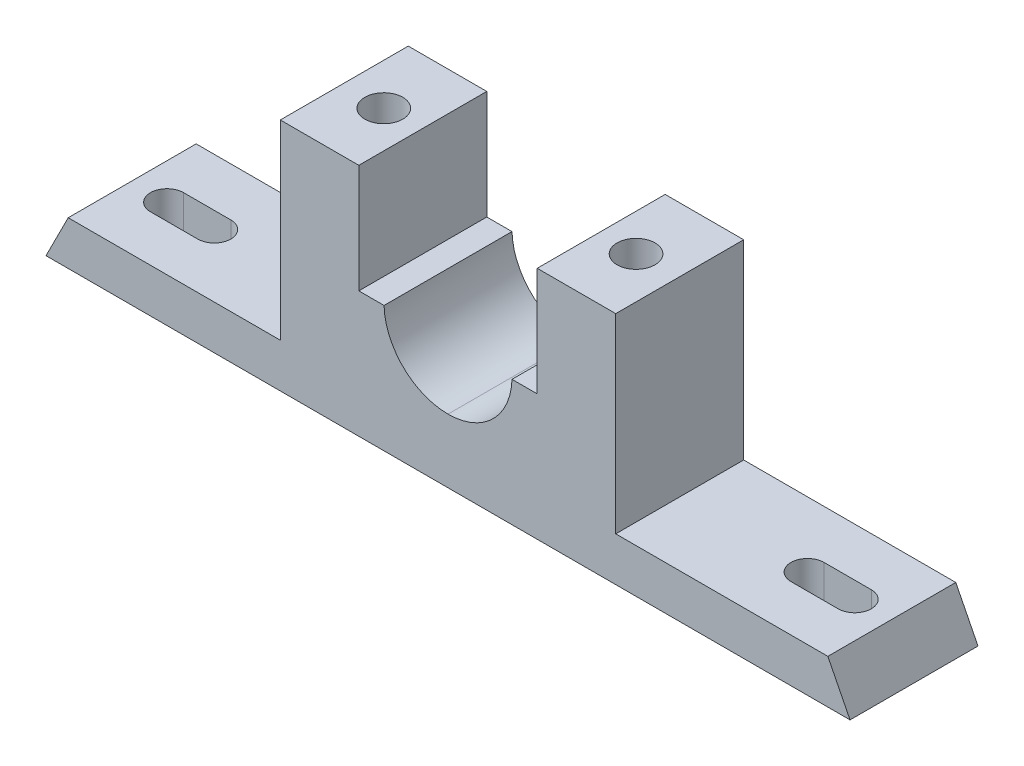
SolidWorks part; units mm, degrees
ref_plane "Front Plane" through (0, 0, 0) normal (0, 0, 1) x (1, 0, 0)
ref_plane "Top Plane" through (0, 0, 0) normal (0, 1, 0) x (1, 0, 0)
ref_plane "Right Plane" through (0, 0, 0) normal (1, 0, 0) x (0, 0, -1)
sketch "Sketch1" plane through (0, 0, 0) normal (0, 0, 1) x (1, 0, 0)
  line L0 (0, -1000) -> (0, 0) construction
  line L1 (0, 0) -> (-79347.474, 0) construction
  line L2 (-201.0841, 0) -> (-189.9813, 22)
  line L3 (-189.9813, 22) -> (-83.8879, 22)
  line L4 (-83.8879, 22) -> (-83.8879, 117.4019)
  line L5 (-83.8879, 117.4019) -> (-44.6133, 117.4019)
  line L6 (-44.6133, 117.4019) -> (-44.6133, 63)
  line L7 (-44.6133, 63) -> (-32, 63)
  line L9 (201.0841, 0) -> (189.9813, 22)
  line L11 (201.0841, 0) -> (-201.0841, 0)
  line L12 (189.9813, 22) -> (83.8879, 22)
  line L13 (83.8879, 22) -> (83.8879, 117.4019)
  line L14 (83.8879, 117.4019) -> (44.6133, 117.4019)
  line L15 (44.6133, 117.4019) -> (44.6133, 63)
  line L16 (44.6133, 63) -> (32, 63)
  line L17 (0, 31.9184) -> (0, 79347.474) construction
  arc A0 (-32, 63) -> (0, 31.9184) centre (-0.0132, 63.9184) ccw
  arc A1 (32, 63) -> (0, 31.9184) centre (0.0132, 63.9184) cw
  dimension "D5" = 32
  dimension "D1" = 22
  dimension "D2" = 63
extrude "Boss-Extrude1" add sketch "Sketch1" along normal blind 64
sketch "Sketch2" plane through (0, 22, 0) normal (0, 1, 0) x (1, 0, 0)
  line L0 (-171.9859, -32.562) -> (-148.3637, -32.562) construction
  line L1 (-171.9859, -24.2735) -> (-148.3637, -24.2735)
  line L2 (-171.9859, -40.8505) -> (-148.3637, -40.8505)
  arc A0 (-171.9859, -24.2735) -> (-171.9859, -40.8505) centre (-171.9859, -32.562) ccw
  arc A1 (-148.3637, -40.8505) -> (-148.3637, -24.2735) centre (-148.3637, -32.562) ccw
  point P2 (-160.1748, -32.562)
extrude "Cut-Extrude1" cut sketch "Sketch2" against normal blind 64
hole_wizard "CBORE for M5 Hex Head Bolt1" positions "Sketch4" profile "Sketch5" counterbore size "M5" standard "ISO"
sketch "Sketch4" plane through (0, 0, 0) normal (0, -1, 0) x (-1, 0, 0)
  line L0 (201.0841, -64) -> (201.0841, 0) construction
  point P0 (63.0841, -33.0361)
  dimension "D1" = 138
sketch "Sketch5" plane through (-63.0841, 0, 33.0361) normal (1, 0, 0) x (0, 0, -1)
  line L0 (0, 0) -> (0, 135.7082)
  line L1 (0, 135.7082) -> (9.5, 130)
  line L2 (9.5, 130) -> (9.5, 12)
  line L3 (9.5, 12) -> (15, 12)
  line L4 (15, 12) -> (15, 0)
  line L5 (15, 0) -> (0, 0)
  line L10 (0, 135.7082) -> (-9.5, 130) construction
  line L11 (0, -6.35) -> (0, 107.95) construction
  dimension "Hole Dia." = 19
  dimension "Hole Depth" = 130
  dimension "C'Bore Dia." = 30
  dimension "C'Bore Depth" = 12
  dimension "Drill Angle" = 118
mirror "Mirror1" about plane through (0, 0, 0) normal (1, 0, 0) of "CBORE for M5 Hex Head Bolt1", "Cut-Extrude1"
